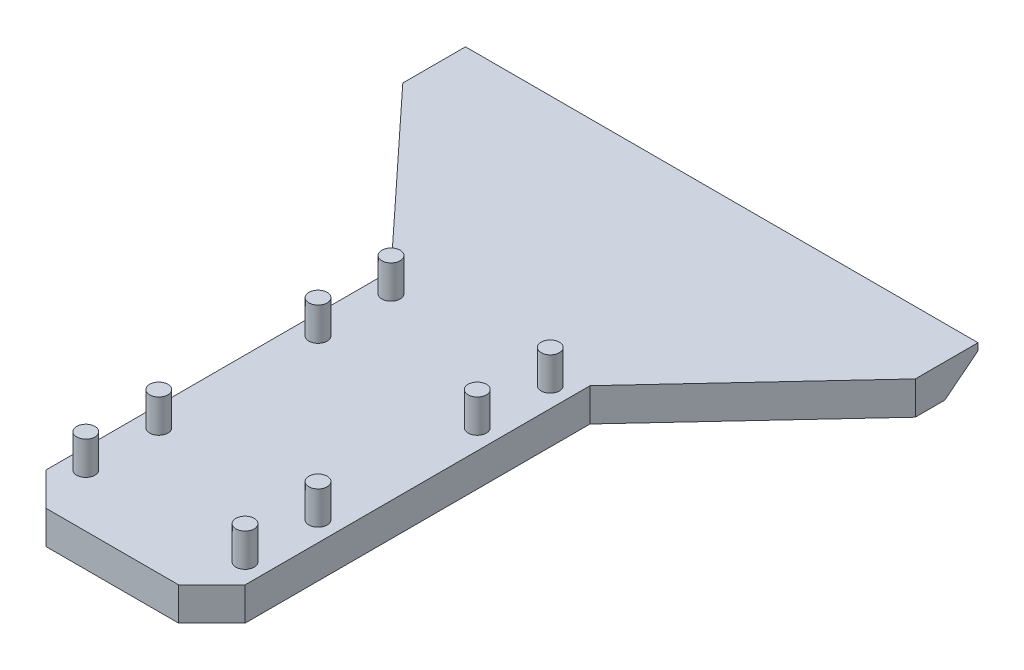
SolidWorks part; units mm, degrees
ref_plane "Front Plane" through (0, 0, 0) normal (0, 0, 1) x (1, 0, 0)
ref_plane "Top Plane" through (0, 0, 0) normal (0, 1, 0) x (1, 0, 0)
ref_plane "Right Plane" through (0, 0, 0) normal (1, 0, 0) x (0, 0, -1)
sketch "Sketch2" plane through (0, 0, 0) normal (0, 1, 0) x (1, 0, 0)
  line L0 (0, -132.715) -> (0, 132.715) construction
  line L1 (-19.05, -74.93) -> (-19.05, -82.55) construction
  line L2 (-19.05, -60.96) -> (-19.05, -68.58) construction
  line L3 (-19.05, -30.48) -> (-19.05, -38.1) construction
  line L4 (-19.05, -16.51) -> (-19.05, -24.13) construction
  line L5 (19.05, -82.55) -> (-19.05, -82.55) construction
  line L6 (-19.05, -82.55) -> (-19.05, -88.9) construction
  line L7 (-19.05, -88.9) -> (19.05, -88.9) construction
  line L8 (19.05, -88.9) -> (19.05, -82.55) construction
  line L9 (-19.05, -74.93) -> (-19.05, -82.55) construction
  line L10 (-19.05, -82.55) -> (19.05, -82.55) construction
  line L11 (19.05, -82.55) -> (19.05, -74.93) construction
  line L12 (19.05, -74.93) -> (-19.05, -74.93) construction
  line L13 (-19.05, -74.93) -> (19.05, -74.93) construction
  line L14 (19.05, -74.93) -> (19.05, -68.58) construction
  line L15 (19.05, -68.58) -> (-19.05, -68.58) construction
  line L16 (-19.05, -68.58) -> (-19.05, -74.93) construction
  line L17 (-19.05, -60.96) -> (-19.05, -68.58) construction
  line L18 (-19.05, -68.58) -> (19.05, -68.58) construction
  line L19 (19.05, -68.58) -> (19.05, -60.96) construction
  line L20 (19.05, -60.96) -> (-19.05, -60.96) construction
  line L21 (-19.05, -16.51) -> (-19.05, -24.13) construction
  line L22 (-19.05, -24.13) -> (19.05, -24.13) construction
  line L23 (19.05, -24.13) -> (19.05, -16.51) construction
  line L24 (19.05, -16.51) -> (-19.05, -16.51) construction
  line L25 (-19.05, -30.48) -> (19.05, -30.48) construction
  line L26 (19.05, -30.48) -> (19.05, -24.13) construction
  line L27 (19.05, -24.13) -> (-19.05, -24.13) construction
  line L28 (-19.05, -24.13) -> (-19.05, -30.48) construction
  line L29 (19.05, -38.1) -> (19.05, -30.48) construction
  line L30 (19.05, -30.48) -> (-19.05, -30.48) construction
  line L31 (-19.05, -30.48) -> (-19.05, -38.1) construction
  line L32 (-19.05, -38.1) -> (19.05, -38.1) construction
  line L33 (-19.05, -60.96) -> (19.05, -60.96) construction
  line L34 (19.05, -60.96) -> (19.05, -38.1) construction
  line L35 (19.05, -38.1) -> (-19.05, -38.1) construction
  line L36 (-19.05, -38.1) -> (-19.05, -60.96) construction
  line L37 (-19.05, -16.51) -> (19.05, -16.51) construction
  line L38 (19.05, -16.51) -> (19.05, 0) construction
  line L39 (19.05, 0) -> (47.625, 0) construction
  line L40 (47.625, 0) -> (76.2, 38.1) construction
  line L41 (76.2, 38.1) -> (76.2, 101.6) construction
  line L42 (76.2, 101.6) -> (38.1, 152.4) construction
  line L43 (38.1, 152.4) -> (-38.1, 152.4) construction
  line L44 (-38.1, 152.4) -> (-76.2, 101.6) construction
  line L45 (-76.2, 101.6) -> (-76.2, 38.1) construction
  line L46 (-76.2, 38.1) -> (-47.625, 0) construction
  line L47 (-47.625, 0) -> (-19.05, 0) construction
  line L48 (-19.05, 0) -> (-19.05, -16.51) construction
  circle A8 centre (-15.24, -78.74) radius 1.905
  circle A9 centre (-15.24, -64.77) radius 1.905
  circle A10 centre (-15.24, -34.29) radius 1.905
  circle A11 centre (-15.24, -20.32) radius 1.905
  circle A12 centre (15.24, -78.74) radius 1.905
  circle A13 centre (15.24, -64.77) radius 1.905
  circle A14 centre (15.24, -34.29) radius 1.905
  circle A15 centre (15.24, -20.32) radius 1.905
  point P0 (0, -88.9)
  point P3 (0, 152.4)
  point P21 (-19.05, -20.32)
  point P23 (-19.05, -34.29)
  point P25 (-19.05, -64.77)
  point P27 (-19.05, -78.74)
  dimension "D1" = 3.81
sketch "Sketch3" plane through (0, 0, 0) normal (0, 1, 0) x (1, 0, 0)
  line L0 (-19.05, 0) -> (-19.05, -16.51) construction
  line L1 (19.05, -16.51) -> (19.05, 0) construction
  line L4 (-19.05, -82.55) -> (-12.7, -88.9)
  line L5 (0, -132.715) -> (0, 132.715) construction
  line L6 (19.05, -82.55) -> (12.7, -88.9)
  line L7 (-49.05, 15.745) -> (-19.05, -16.51)
  line L8 (19.05, -16.51) -> (49.05, 15.745)
  line L11 (-19.05, -8.255) -> (-19.05, -16.51) construction
  line L12 (19.05, -16.51) -> (19.05, -8.255) construction
  line L26 (-19.05, -88.9) -> (19.05, -88.9) construction
  line L27 (-19.05, -68.58) -> (-19.05, -74.93) construction
  line L28 (-19.05, -74.93) -> (-19.05, -82.55) construction
  line L30 (19.05, -82.55) -> (19.05, -74.93) construction
  line L32 (19.05, -74.93) -> (19.05, -68.58) construction
  line L33 (19.05, -68.58) -> (19.05, -60.96) construction
  line L35 (-19.05, -60.96) -> (-19.05, -68.58) construction
  line L37 (-19.05, -38.1) -> (-19.05, -60.96) construction
  line L38 (19.05, -60.96) -> (19.05, -38.1) construction
  line L39 (19.05, -24.13) -> (19.05, -16.51) construction
  line L40 (19.05, -30.48) -> (19.05, -24.13) construction
  line L41 (-19.05, -30.48) -> (-19.05, -38.1) construction
  line L44 (-19.05, -24.13) -> (-19.05, -30.48) construction
  line L45 (-19.05, -16.51) -> (-19.05, -24.13) construction
  line L49 (-12.7, -88.9) -> (12.7, -88.9)
  line L50 (-19.05, -68.58) -> (-19.05, -74.93)
  line L51 (-19.05, -74.93) -> (-19.05, -82.55)
  line L53 (19.05, -82.55) -> (19.05, -74.93)
  line L55 (19.05, -74.93) -> (19.05, -68.58)
  line L56 (19.05, -68.58) -> (19.05, -60.96)
  line L58 (-19.05, -60.96) -> (-19.05, -68.58)
  line L60 (-19.05, -38.1) -> (-19.05, -60.96)
  line L61 (19.05, -60.96) -> (19.05, -38.1)
  line L62 (19.05, -24.13) -> (19.05, -16.51)
  line L63 (19.05, -30.48) -> (19.05, -24.13)
  line L64 (-19.05, -30.48) -> (-19.05, -38.1)
  line L67 (-19.05, -24.13) -> (-19.05, -30.48)
  line L68 (-19.05, -16.51) -> (-19.05, -24.13)
  line L70 (19.05, -38.1) -> (19.05, -30.48) construction
  line L71 (19.05, -38.1) -> (19.05, -30.48)
  line L72 (19.05, -8.255) -> (49.05, 15.745) construction
  line L73 (49.05, 15.745) -> (49.05, 27.745)
  line L74 (49.05, 27.745) -> (-49.05, 27.745)
  line L75 (-49.05, 27.745) -> (-49.05, 15.745)
  line L76 (-49.05, 15.745) -> (-19.05, -8.255) construction
  circle A0 centre (-15.24, -78.74) radius 1.905 construction
  circle A1 centre (15.24, -78.74) radius 1.905 construction
  circle A2 centre (15.24, -64.77) radius 1.905 construction
  circle A3 centre (-15.24, -64.77) radius 1.905 construction
  circle A4 centre (-15.24, -20.32) radius 1.905 construction
  circle A5 centre (15.24, -20.32) radius 1.905 construction
  circle A6 centre (15.24, -34.29) radius 1.905 construction
  circle A7 centre (-15.24, -34.29) radius 1.905 construction
  circle A8 centre (-15.24, -78.74) radius 1.905
  circle A9 centre (15.24, -78.74) radius 1.905
  circle A10 centre (15.24, -64.77) radius 1.905
  circle A11 centre (-15.24, -64.77) radius 1.905
  circle A12 centre (-15.24, -20.32) radius 1.905
  circle A13 centre (15.24, -20.32) radius 1.905
  circle A14 centre (15.24, -34.29) radius 1.905
  circle A15 centre (-15.24, -34.29) radius 1.905
  point P56 (0, 27.745)
  dimension "D1" = 24
  dimension "D2" = 30
  dimension "D3" = 12
  dimension "D4" = 12
  dimension "D5" = 80.645
  dimension "D6" = 6.35
extrude "Boss-Extrude1" add sketch "Sketch3" along normal blind 6.35
sketch "Sketch4" plane through (-49.05, 0, 0) normal (-1, 0, 0) x (0, 0, 1)
  line L1 (-21.395, 0) -> (-27.745, 0)
  line L3 (-27.745, 0) -> (-15.745, 0) construction
  line L4 (-27.745, 0) -> (-27.745, 5)
  line L5 (-27.745, 6.35) -> (-27.745, 0) construction
  line L6 (-27.745, 5) -> (-21.395, 0)
  dimension "D1" = 5
  dimension "D2" = 6.35
extrude "Cut-Extrude1" cut sketch "Sketch4" against normal through all
sketch "Sketch5" plane through (0, 0, 0) normal (0, -1, 0) x (1, 0, 0)
  circle A0 centre (-15.24, 20.32) radius 1.905 construction
  circle A1 centre (-15.24, 34.29) radius 1.905 construction
  circle A2 centre (15.24, 20.32) radius 1.905 construction
  circle A3 centre (15.24, 34.29) radius 1.905 construction
  circle A4 centre (15.24, 64.77) radius 1.905 construction
  circle A5 centre (15.24, 78.74) radius 1.905 construction
  circle A6 centre (-15.24, 64.77) radius 1.905 construction
  circle A7 centre (-15.24, 78.74) radius 1.905 construction
  circle A8 centre (-15.24, 20.32) radius 1.905
  circle A9 centre (-15.24, 34.29) radius 1.905
  circle A10 centre (15.24, 20.32) radius 1.905
  circle A11 centre (15.24, 34.29) radius 1.905
  circle A12 centre (15.24, 64.77) radius 1.905
  circle A13 centre (15.24, 78.74) radius 1.905
  circle A14 centre (-15.24, 64.77) radius 1.905
  circle A15 centre (-15.24, 78.74) radius 1.905
extrude "Boss-Extrude2" add sketch "Sketch5" against normal blind 12.7
sketch "Sketch6" plane through (0, 12.7, 0) normal (0, 1, 0) x (1, 0, 0)
  circle A0 centre (-15.24, -78.74) radius 1.905 construction
  circle A1 centre (15.24, -78.74) radius 1.905 construction
  circle A2 centre (15.24, -64.77) radius 1.905 construction
  circle A3 centre (-15.24, -64.77) radius 1.905 construction
  circle A4 centre (-15.24, -34.29) radius 1.905 construction
  circle A5 centre (15.24, -34.29) radius 1.905 construction
  circle A6 centre (15.24, -20.32) radius 1.905 construction
  circle A7 centre (-15.24, -20.32) radius 1.905 construction
  circle A8 centre (-15.24, -78.74) radius 1.905
  circle A9 centre (15.24, -78.74) radius 1.905
  circle A10 centre (15.24, -64.77) radius 1.905
  circle A11 centre (-15.24, -64.77) radius 1.905
  circle A12 centre (-15.24, -34.29) radius 1.905
  circle A13 centre (15.24, -34.29) radius 1.905
  circle A14 centre (15.24, -20.32) radius 1.905
  circle A15 centre (-15.24, -20.32) radius 1.905
  circle A16 centre (-15.24, -20.32) radius 1.75
  circle A17 centre (15.24, -20.32) radius 1.75
  circle A18 centre (15.24, -34.29) radius 1.75
  circle A19 centre (-15.24, -34.29) radius 1.75
  circle A20 centre (-15.24, -64.77) radius 1.75
  circle A21 centre (15.24, -64.77) radius 1.75
  circle A22 centre (15.24, -78.74) radius 1.75
  circle A23 centre (-15.24, -78.74) radius 1.75
  dimension "D1" = 3.5
extrude "Cut-Extrude2" cut sketch "Sketch6" against normal up to surface (6.35 mm away) up to face at (15.24, 6.35, 36.195)
